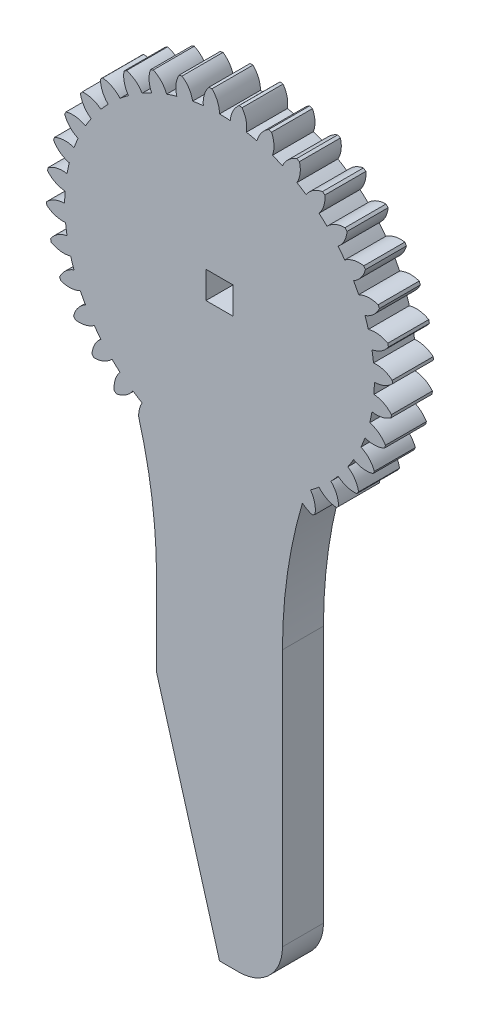
SolidWorks part; units mm, degrees
ref_plane "Front Plane" through (0, 0, 0) normal (0, 0, 1) x (1, 0, 0)
ref_plane "Top Plane" through (0, 0, 0) normal (0, 1, 0) x (1, 0, 0)
ref_plane "Right Plane" through (0, 0, 0) normal (1, 0, 0) x (0, 0, -1)
sketch "Sketch3" plane through (0, 0, 0) normal (0, 0, 1) x (1, 0, 0)
  line L0 (-7.3156, -41.831) -> (0, -67.231)
  line L1 (-1.5748, -1.5748) -> (1.5748, -1.5748)
  line L2 (-1.5748, -1.5748) -> (-1.5748, 1.5748)
  line L3 (-1.5748, 1.5748) -> (1.5748, 1.5748)
  line L4 (1.5748, -1.5748) -> (1.5748, 1.5748)
  line L5 (-1.5748, -1.5748) -> (1.5748, 1.5748) construction
  line L6 (-1.5748, 1.5748) -> (1.5748, -1.5748) construction
  line L8 (-7.3156, -32.2661) -> (-7.3156, -41.831)
  line L9 (0, -67.231) -> (2.2356, -67.231)
  line L10 (7.3156, -32.2661) -> (7.3156, -62.151)
  line L12 (-11.7543, -10.3857) -> (11.7543, -10.3857)
  line L13 (-11.7543, -10.3857) -> (-11.1898, -11.8217)
  line L15 (11.1898, -11.8217) -> (11.7543, -10.3857)
  arc A0 (2.2356, -67.231) -> (7.3156, -62.151) centre (2.2356, -62.151) ccw
  arc A1 (7.3156, -32.2661) -> (11.1898, -11.8217) centre (63.1956, -32.2661) cw
  arc A2 (-7.3156, -32.2661) -> (-11.1898, -11.8217) centre (-63.1956, -32.2661) ccw
  point P0 (0, 0)
  point P12 (7.3156, -67.231)
  point P19 (0, -10.3857)
  arc B0 (-17.4517, 4.3512) -> (-17.7128, 3.1232) centre (0, 0) ccw
  arc B1 (-17.7128, -3.1232) -> (-19.6276, -4.3513) centre (-17.2004, -6.0289) ccw
  arc B2 (-19.5486, -4.6932) -> (-17.2893, -4.9576) centre (-18.1025, -2.1215) ccw
  arc B3 (-17.2893, -4.9576) -> (-16.9013, -6.1516) centre (0, 0) ccw
  arc B4 (-17.986, 0) -> (-20.085, -0.8769) centre (-17.986, -2.9504) ccw
  arc B5 (-17.9422, 1.2546) -> (-17.986, 0) centre (0, 0) ccw
  arc B6 (-17.7128, 3.1232) -> (-19.9321, 2.6241) centre (-18.2251, 0.2176) ccw
  arc B7 (-19.9749, 2.2758) -> (-17.9422, 1.2546) centre (-17.7364, 4.1979) ccw
  arc B8 (-19.2762, 5.7099) -> (-17.4517, 4.3512) centre (-16.738, 7.214) ccw
  arc B9 (-14.9111, 10.0576) -> (-15.5763, 8.993) centre (0, 0) ccw
  arc B10 (-16.1608, 11.9584) -> (-14.9111, 10.0576) centre (-13.2612, 12.5037) ccw
  arc B11 (-15.9497, 12.2386) -> (-16.1608, 11.9584) centre (0, 0) ccw
  arc B12 (-13.7781, 11.5612) -> (-15.9497, 12.2386) centre (-15.6746, 9.301) ccw
  arc B13 (-12.938, 12.4941) -> (-13.7781, 11.5612) centre (0, 0) ccw
  arc B14 (-13.8387, 14.583) -> (-12.938, 12.4941) centre (-10.8885, 14.6165) ccw
  arc B15 (-13.5821, 14.8223) -> (-13.8387, 14.583) centre (0, 0) ccw
  arc B16 (-11.5612, 13.7781) -> (-13.5821, 14.8223) centre (-13.8214, 11.8816) ccw
  arc B17 (-10.5719, 14.551) -> (-11.5612, 13.7781) centre (0, 0) ccw
  arc B18 (-11.0962, 16.7645) -> (-10.5719, 14.551) centre (-8.1849, 16.2852) ccw
  arc B19 (-10.8019, 16.9556) -> (-11.0962, 16.7645) centre (0, 0) ccw
  arc B20 (-8.993, 15.5763) -> (-10.8019, 16.9556) centre (-11.5482, 14.1011) ccw
  arc B21 (-7.8845, 16.1657) -> (-8.993, 15.5763) centre (0, 0) ccw
  arc B22 (-8.0165, 18.4367) -> (-7.8845, 16.1657) centre (-5.2327, 17.4591) ccw
  arc B23 (-7.6935, 18.5738) -> (-8.0165, 18.4367) centre (0, 0) ccw
  arc B24 (-6.1516, 16.9013) -> (-7.6935, 18.5738) centre (-8.9241, 15.8922) ccw
  arc B25 (-4.9576, 17.2893) -> (-6.1516, 16.9013) centre (0, 0) ccw
  arc B26 (-4.6932, 19.5486) -> (-4.9576, 17.2893) centre (-2.1215, 18.1025) ccw
  arc B27 (-4.3513, 19.6276) -> (-4.6932, 19.5486) centre (0, 0) ccw
  arc B28 (-3.1232, 17.7128) -> (-4.3513, 19.6276) centre (-6.0289, 17.2004) ccw
  arc B29 (-1.88, 17.8875) -> (-3.1232, 17.7128) centre (0, 0) ccw
  arc B30 (-1.2273, 20.0666) -> (-1.88, 17.8875) centre (1.0542, 18.1959) ccw
  arc B31 (-0.8769, 20.085) -> (-1.2273, 20.0666) centre (0, 0) ccw
  arc B32 (0, 17.986) -> (-0.8769, 20.085) centre (-2.9504, 17.986) ccw
  arc B33 (1.2546, 17.9422) -> (0, 17.986) centre (0, 0) ccw
  arc B34 (2.2758, 19.9749) -> (1.2546, 17.9422) centre (4.1979, 17.7364) ccw
  arc B35 (2.6241, 19.9321) -> (2.2758, 19.9749) centre (0, 0) ccw
  arc B36 (3.1232, 17.7128) -> (2.6241, 19.9321) centre (0.2176, 18.2251) ccw
  arc B37 (4.3512, 17.4517) -> (3.1232, 17.7128) centre (0, 0) ccw
  arc B38 (5.7099, 19.2762) -> (4.3512, 17.4517) centre (7.214, 16.738) ccw
  arc B39 (6.0454, 19.1736) -> (5.7099, 19.2762) centre (0, 0) ccw
  arc B40 (6.1516, 16.9013) -> (6.0454, 19.1736) centre (3.3791, 17.9104) ccw
  arc B41 (7.3156, 16.431) -> (6.1516, 16.9013) centre (0, 0) ccw
  arc B42 (8.9704, 17.9918) -> (7.3156, 16.431) centre (10.0109, 15.231) ccw
  arc B43 (9.283, 17.8326) -> (8.9704, 17.9918) centre (0, 0) ccw
  arc B44 (8.993, 15.5763) -> (9.283, 17.8326) centre (6.4378, 17.0516) ccw
  arc B45 (10.0576, 14.9111) -> (8.993, 15.5763) centre (0, 0) ccw
  arc B46 (11.9584, 16.1608) -> (10.0576, 14.9111) centre (12.5037, 13.2612) ccw
  arc B47 (12.2386, 15.9497) -> (11.9584, 16.1608) centre (0, 0) ccw
  arc B48 (11.5612, 13.7781) -> (12.2386, 15.9497) centre (9.301, 15.6746) ccw
  arc B49 (12.4941, 12.938) -> (11.5612, 13.7781) centre (0, 0) ccw
  arc B50 (14.583, 13.8387) -> (12.4941, 12.938) centre (14.6165, 10.8885) ccw
  arc B51 (14.8223, 13.5821) -> (14.583, 13.8387) centre (0, 0) ccw
  arc B52 (13.7781, 11.5612) -> (14.8223, 13.5821) centre (11.8816, 13.8214) ccw
  arc B53 (14.551, 10.5719) -> (13.7781, 11.5612) centre (0, 0) ccw
  arc B54 (16.7645, 11.0962) -> (14.551, 10.5719) centre (16.2852, 8.1849) ccw
  arc B55 (16.9556, 10.8019) -> (16.7645, 11.0962) centre (0, 0) ccw
  arc B56 (15.5763, 8.993) -> (16.9556, 10.8019) centre (14.1011, 11.5482) ccw
  arc B57 (16.1657, 7.8845) -> (15.5763, 8.993) centre (0, 0) ccw
  arc B58 (18.4367, 8.0165) -> (16.1657, 7.8845) centre (17.4591, 5.2327) ccw
  arc B59 (18.5738, 7.6935) -> (18.4367, 8.0165) centre (0, 0) ccw
  arc B60 (16.9013, 6.1516) -> (18.5738, 7.6935) centre (15.8922, 8.9241) ccw
  arc B61 (17.2893, 4.9576) -> (16.9013, 6.1516) centre (0, 0) ccw
  arc B62 (19.5486, 4.6932) -> (17.2893, 4.9576) centre (18.1025, 2.1215) ccw
  arc B63 (19.6276, 4.3513) -> (19.5486, 4.6932) centre (0, 0) ccw
  arc B64 (17.7128, 3.1232) -> (19.6276, 4.3513) centre (17.2004, 6.0289) ccw
  arc B65 (17.8875, 1.88) -> (17.7128, 3.1232) centre (0, 0) ccw
  arc B66 (20.0666, 1.2273) -> (17.8875, 1.88) centre (18.1959, -1.0542) ccw
  arc B67 (20.085, 0.8769) -> (20.0666, 1.2273) centre (0, 0) ccw
  arc B68 (17.986, 0) -> (20.085, 0.8769) centre (17.986, 2.9504) ccw
  arc B69 (17.9422, -1.2546) -> (17.986, 0) centre (0, 0) ccw
  arc B70 (19.9749, -2.2758) -> (17.9422, -1.2546) centre (17.7364, -4.1979) ccw
  arc B71 (19.9321, -2.6241) -> (19.9749, -2.2758) centre (0, 0) ccw
  arc B72 (17.7128, -3.1232) -> (19.9321, -2.6241) centre (18.2251, -0.2176) ccw
  arc B73 (17.4517, -4.3512) -> (17.7128, -3.1232) centre (0, 0) ccw
  arc B74 (19.2762, -5.7099) -> (17.4517, -4.3512) centre (16.738, -7.214) ccw
  arc B75 (19.1736, -6.0454) -> (19.2762, -5.7099) centre (0, 0) ccw
  arc B76 (16.9013, -6.1516) -> (19.1736, -6.0454) centre (17.9104, -3.3791) ccw
  arc B77 (16.431, -7.3156) -> (16.9013, -6.1516) centre (0, 0) ccw
  arc B78 (17.9918, -8.9704) -> (16.431, -7.3156) centre (15.231, -10.0109) ccw
  arc B79 (17.8326, -9.283) -> (17.9918, -8.9704) centre (0, 0) ccw
  arc B80 (15.5763, -8.993) -> (17.8326, -9.283) centre (17.0516, -6.4378) ccw
  arc B81 (14.9111, -10.0576) -> (15.5763, -8.993) centre (0, 0) ccw
  arc B82 (16.1608, -11.9584) -> (14.9111, -10.0576) centre (13.2612, -12.5037) ccw
  arc B83 (15.9497, -12.2386) -> (16.1608, -11.9584) centre (0, 0) ccw
  arc B84 (13.7781, -11.5612) -> (15.9497, -12.2386) centre (15.6746, -9.301) ccw
  arc B85 (12.938, -12.4941) -> (13.7781, -11.5612) centre (0, 0) ccw
  arc B86 (13.8387, -14.583) -> (12.938, -12.4941) centre (10.8885, -14.6165) ccw
  arc B87 (13.5821, -14.8223) -> (13.8387, -14.583) centre (0, 0) ccw
  arc B88 (11.5612, -13.7781) -> (13.5821, -14.8223) centre (13.8214, -11.8816) ccw
  arc B89 (10.5719, -14.551) -> (11.5612, -13.7781) centre (0, 0) ccw
  arc B90 (11.0962, -16.7645) -> (10.5719, -14.551) centre (8.1849, -16.2852) ccw
  arc B91 (10.8019, -16.9556) -> (11.0962, -16.7645) centre (0, 0) ccw
  arc B92 (8.993, -15.5763) -> (10.8019, -16.9556) centre (11.5482, -14.1011) ccw
  arc B93 (7.8845, -16.1657) -> (8.993, -15.5763) centre (0, 0) ccw
  arc B94 (8.0165, -18.4367) -> (7.8845, -16.1657) centre (5.2327, -17.4591) ccw
  arc B95 (7.6935, -18.5738) -> (8.0165, -18.4367) centre (0, 0) ccw
  arc B96 (6.1516, -16.9013) -> (7.6935, -18.5738) centre (8.9241, -15.8922) ccw
  arc B97 (4.9576, -17.2893) -> (6.1516, -16.9013) centre (0, 0) ccw
  arc B98 (4.6932, -19.5486) -> (4.9576, -17.2893) centre (2.1215, -18.1025) ccw
  arc B99 (4.3513, -19.6276) -> (4.6932, -19.5486) centre (0, 0) ccw
  arc B100 (3.1232, -17.7128) -> (4.3513, -19.6276) centre (6.0289, -17.2004) ccw
  arc B101 (1.88, -17.8875) -> (3.1232, -17.7128) centre (0, 0) ccw
  arc B102 (1.2273, -20.0666) -> (1.88, -17.8875) centre (-1.0542, -18.1959) ccw
  arc B103 (0.8769, -20.085) -> (1.2273, -20.0666) centre (0, 0) ccw
  arc B104 (0, -17.986) -> (0.8769, -20.085) centre (2.9504, -17.986) ccw
  arc B105 (-1.2546, -17.9422) -> (0, -17.986) centre (0, 0) ccw
  arc B106 (-2.2758, -19.9749) -> (-1.2546, -17.9422) centre (-4.1979, -17.7364) ccw
  arc B107 (-2.6241, -19.9321) -> (-2.2758, -19.9749) centre (0, 0) ccw
  arc B108 (-3.1232, -17.7128) -> (-2.6241, -19.9321) centre (-0.2176, -18.2251) ccw
  arc B109 (-4.3512, -17.4517) -> (-3.1232, -17.7128) centre (0, 0) ccw
  arc B110 (-5.7099, -19.2762) -> (-4.3512, -17.4517) centre (-7.214, -16.738) ccw
  arc B111 (-6.0454, -19.1736) -> (-5.7099, -19.2762) centre (0, 0) ccw
  arc B112 (-6.1516, -16.9013) -> (-6.0454, -19.1736) centre (-3.3791, -17.9104) ccw
  arc B113 (-7.3156, -16.431) -> (-6.1516, -16.9013) centre (0, 0) ccw
  arc B114 (-8.9704, -17.9918) -> (-7.3156, -16.431) centre (-10.0109, -15.231) ccw
  arc B115 (-9.283, -17.8326) -> (-8.9704, -17.9918) centre (0, 0) ccw
  arc B116 (-8.993, -15.5763) -> (-9.283, -17.8326) centre (-6.4378, -17.0516) ccw
  arc B117 (-10.0576, -14.9111) -> (-8.993, -15.5763) centre (0, 0) ccw
  arc B118 (-11.9584, -16.1608) -> (-10.0576, -14.9111) centre (-12.5037, -13.2612) ccw
  arc B119 (-12.2386, -15.9497) -> (-11.9584, -16.1608) centre (0, 0) ccw
  arc B120 (-11.5612, -13.7781) -> (-12.2386, -15.9497) centre (-9.301, -15.6746) ccw
  arc B121 (-12.4941, -12.938) -> (-11.5612, -13.7781) centre (0, 0) ccw
  arc B122 (-14.583, -13.8387) -> (-12.4941, -12.938) centre (-14.6165, -10.8885) ccw
  arc B123 (-14.8223, -13.5821) -> (-14.583, -13.8387) centre (0, 0) ccw
  arc B124 (-13.7781, -11.5612) -> (-14.8223, -13.5821) centre (-11.8816, -13.8214) ccw
  arc B125 (-14.551, -10.5719) -> (-13.7781, -11.5612) centre (0, 0) ccw
  arc B126 (-16.7645, -11.0962) -> (-14.551, -10.5719) centre (-16.2852, -8.1849) ccw
  arc B127 (-16.9556, -10.8019) -> (-16.7645, -11.0962) centre (0, 0) ccw
  arc B128 (-15.5763, -8.993) -> (-16.9556, -10.8019) centre (-14.1011, -11.5482) ccw
  arc B129 (-16.1657, -7.8845) -> (-15.5763, -8.993) centre (0, 0) ccw
  arc B130 (-18.4367, -8.0165) -> (-16.1657, -7.8845) centre (-17.4591, -5.2327) ccw
  arc B131 (-18.5738, -7.6935) -> (-18.4367, -8.0165) centre (0, 0) ccw
  arc B132 (-16.9013, -6.1516) -> (-18.5738, -7.6935) centre (-15.8922, -8.9241) ccw
  arc B133 (-19.6276, -4.3513) -> (-19.5486, -4.6932) centre (0, 0) ccw
  arc B134 (-17.8875, -1.88) -> (-17.7128, -3.1232) centre (0, 0) ccw
  arc B135 (-20.0666, -1.2273) -> (-17.8875, -1.88) centre (-18.1959, 1.0542) ccw
  arc B136 (-20.085, -0.8769) -> (-20.0666, -1.2273) centre (0, 0) ccw
  arc B137 (-19.9321, 2.6241) -> (-19.9749, 2.2758) centre (0, 0) ccw
  arc B138 (-19.1736, 6.0454) -> (-19.2762, 5.7099) centre (0, 0) ccw
  arc B139 (-16.9013, 6.1516) -> (-19.1736, 6.0454) centre (-17.9104, 3.3791) ccw
  arc B140 (-16.431, 7.3156) -> (-16.9013, 6.1516) centre (0, 0) ccw
  arc B141 (-17.9918, 8.9704) -> (-16.431, 7.3156) centre (-15.231, 10.0109) ccw
  arc B142 (-17.8326, 9.283) -> (-17.9918, 8.9704) centre (0, 0) ccw
  arc B143 (-15.5763, 8.993) -> (-17.8326, 9.283) centre (-17.0516, 6.4378) ccw
sketch_block_instance "VEX-36-TOOTH-GEAR-b-1"
sketch_block "VEX-36-TOOTH-GEAR-b"
other "DetailItem3"
other "DetailItem4" parameters "D3"=5.08, "D2"=55.88, "D1"=3.0671
extrude "Boss-Extrude2" add sketch "Sketch3" along normal blind 4.7625 contours B9 B143 B142 B141 B140 B139 B138 B8 B0 B6 B137 B7 B5 B4 B136 B135 B134 B1 B133 B2 B3 B132 B131 B130 B129 B128 B127 B126 B125 B124 B123 B122 B121 B120 B119 B118 A2 L13 L12 L15 A1 B92 B91 B90 B89 B88 B87 B86 B85 B84 B83 | A2 B118 B117 B116 B115 B114 B113 B112 B111 B110 B109 B108 B107 B106 B105 B104 B103 B102 B101 B100 B99 B98 B97 B96 B95 B94 B93 B92 A1 L15 L12 L13 | B115 A2 L8 L0 L9 A0 L10 A1 B92 B93 B94 B95 B96 B97 B98 B99 B100 B101 B102 B103 B104 B105 B106 B107 B108 B109 B110 B111 B112 B113 B114
sketch "Sketch4" plane through (0, 0, 4.7625) normal (0, 0, 1) x (1, 0, 0)
  circle A0 centre (0, 0) radius 2.2271
